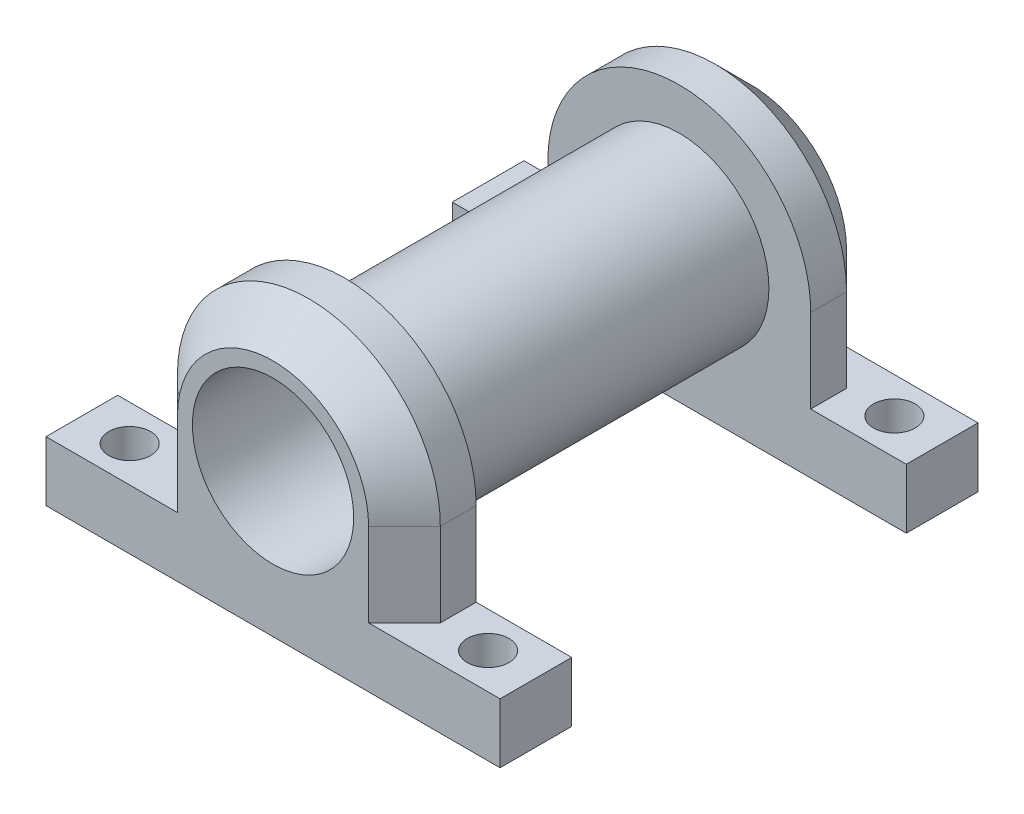
SolidWorks part; units mm, degrees
ref_plane "Front Plane" through (0, 0, 0) normal (0, 0, 1) x (1, 0, 0)
ref_plane "Top Plane" through (0, 0, 0) normal (0, 1, 0) x (1, 0, 0)
ref_plane "Right Plane" through (0, 0, 0) normal (1, 0, 0) x (0, 0, -1)
sketch "Sketch1" plane through (0, 0, 0) normal (0, 0, 1) x (1, 0, 0)
  line L0 (-11, 0) -> (-11, -7)
  line L1 (-11, -12) -> (11, -12)
  line L2 (11, -7) -> (11, 0)
  line L3 (-11, -7) -> (11, -7) construction
  line L4 (-11, -12) -> (-19, -12)
  line L6 (-11, -7) -> (-19, -7)
  line L7 (-19, -12) -> (-19, -7)
  line L8 (11, -12) -> (19, -12)
  line L10 (11, -7) -> (19, -7)
  line L11 (19, -12) -> (19, -7)
  arc A0 (11, 0) -> (-11, 0) centre (0, 0) ccw
  dimension "D1" = 22
  dimension "D2" = 12
  dimension "D3" = 8
  dimension "D4" = 5
extrude "Boss-Extrude1" add sketch "Sketch1" along normal blind 6
sketch "Sketch2" plane through (0, 0, 6) normal (0, 0, 1) x (1, 0, 0)
  circle A0 centre (0, 0) radius 7.5
  dimension "D1" = 15
extrude "Boss-Extrude2" add sketch "Sketch2" along normal blind 28
sketch "Sketch3" plane through (0, 0, 34) normal (0, 0, 1) x (1, 0, 0)
  line L3 (-11, 0) -> (-11, -7)
  line L4 (-19, -12) -> (19, -12)
  line L5 (11, -7) -> (11, 0)
  line L6 (-11, 0) -> (-11, -7)
  line L7 (-19, -12) -> (19, -12)
  line L8 (11, -7) -> (11, 0)
  line L13 (-19, -7) -> (-19, -12)
  line L14 (-19, -7) -> (-19, -12)
  line L15 (19, -12) -> (19, -7)
  line L16 (19, -12) -> (19, -7)
  line L17 (19, -7) -> (11, -7)
  line L18 (19, -7) -> (11, -7)
  line L19 (-11, -7) -> (-19, -7)
  line L20 (-11, -7) -> (-19, -7)
  arc A2 (11, 0) -> (-11, 0) centre (0, 0) ccw
  arc A3 (11, 0) -> (-11, 0) centre (0, 0) ccw
  dimension "D1" = 0
extrude "Boss-Extrude3" add sketch "Sketch3" along normal blind 6
sketch "Sketch4" plane through (0, 0, 40) normal (0, 0, 1) x (1, 0, 0)
  circle A0 centre (0, 0) radius 6.75
  dimension "D1" = 13.5
extrude "Cut-Extrude1" cut sketch "Sketch4" against normal through all
sketch "Sketch5" plane through (0, 0, 0) normal (0, 0, -1) x (-1, 0, 0)
  line L0 (19, -12) -> (-19, -12) construction
  line L1 (-11.5, -12) -> (11.5, -12)
  line L2 (-11.5, -12) -> (-11.5, -9)
  line L3 (-11.5, -9) -> (11.5, -9)
  line L4 (11.5, -12) -> (11.5, -9)
  line L5 (0, -9) -> (0, 0) construction
  dimension "D1" = 23
  dimension "D2" = 3
extrude "Cut-Extrude2" [suppressed] cut sketch "Sketch5" against normal through all and the other way through all
sketch "Sketch6" plane through (0, -7, 0) normal (0, 1, 0) x (1, 0, 0)
  line L0 (-15, -3) -> (15, -3) construction
  line L3 (0, -3) -> (0, 0) construction
  circle A0 centre (-15, -3) radius 1.75
  circle A1 centre (15, -3) radius 1.75
  circle A2 centre (15, -37) radius 1.75
  circle A3 centre (-15, -37) radius 1.75
  dimension "D3" = 3.5
  dimension "D1" = 30
  dimension "D2" = 3
  dimension "D4" = 2
extrude "Cut-Extrude3" cut sketch "Sketch6" against normal through all
chamfer "Chamfer1" distance 3 angle 45 6 edges at (11, -3.5, 40) (0, 11, 40) (-11, -3.5, 40) (11, -3.5, 0) (0, 11, 0) (-11, -3.5, 0)
